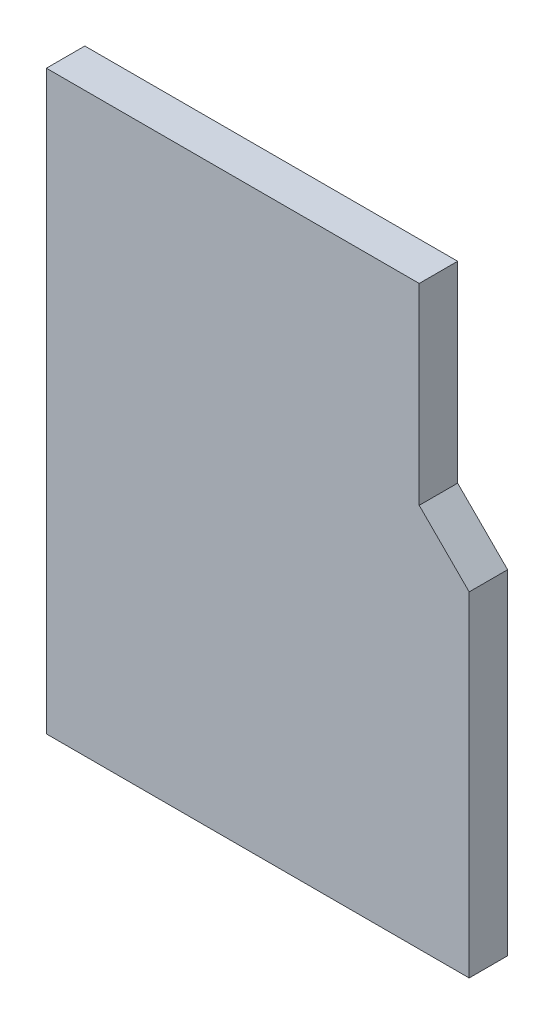
SolidWorks part; units mm, degrees
material "acero"
ref_plane "Alzado" through (0, 0, 0) normal (0, 0, 1) x (1, 0, 0)
ref_plane "Planta" through (0, 0, 0) normal (0, 1, 0) x (1, 0, 0)
ref_plane "Vista lateral" through (0, 0, 0) normal (1, 0, 0) x (0, 0, -1)
sketch "Croquis1" plane through (0, 0, 0) normal (0, 0, 1) x (1, 0, 0)
  line L0 (0, 0) -> (0, 15)
  line L1 (0, 15) -> (9.7, 15)
  line L2 (9.7, 15) -> (9.7, 10)
  line L3 (9.7, 10) -> (11, 8.7)
  line L4 (11, 8.7) -> (11, 0)
  line L5 (11, 0) -> (0, 0)
  dimension "D1" = 11
  dimension "D2" = 15
  dimension "D3" = 9.7
  dimension "D4" = 10
  dimension "D5" = 135
extrude "Saliente-Extruir1" add sketch "Croquis1" along normal blind 1
